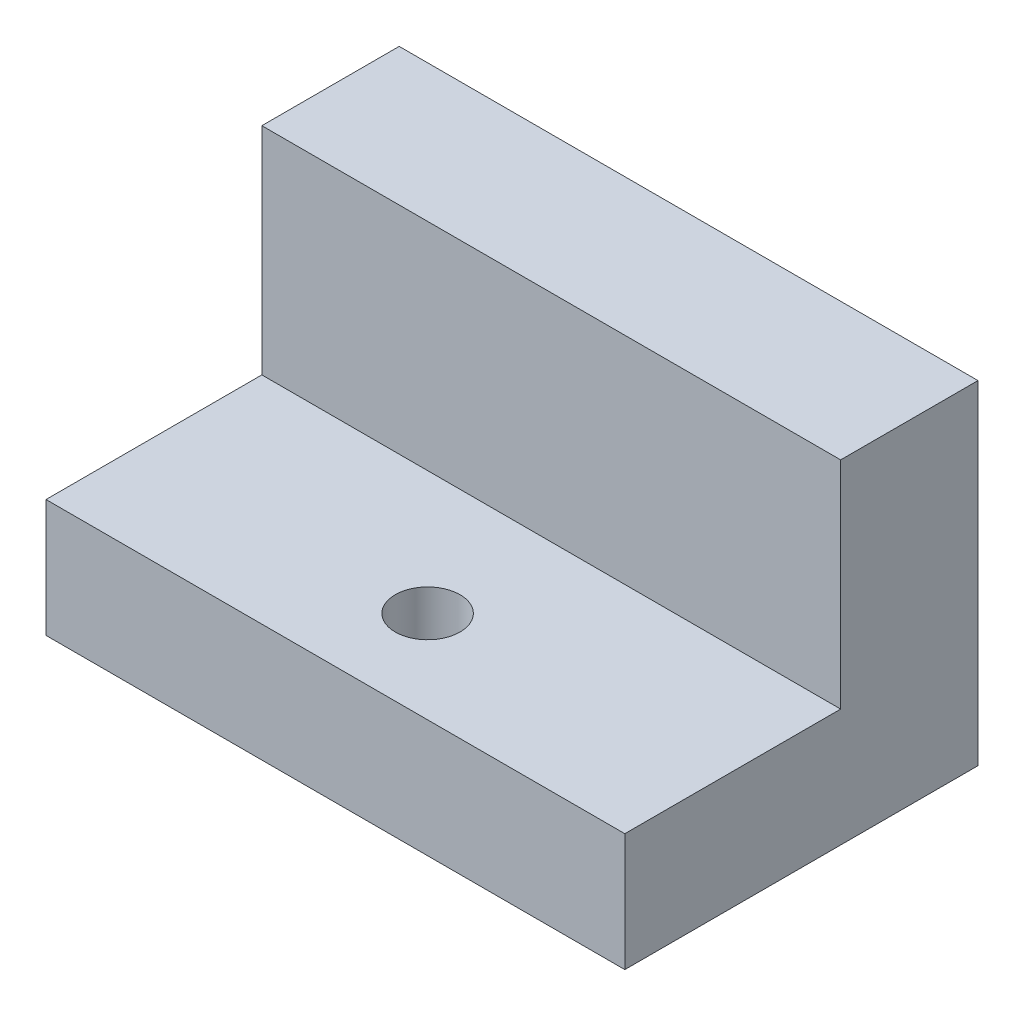
SolidWorks part; units mm, degrees
ref_plane "Front Plane" through (0, 0, 0) normal (0, 0, 1) x (1, 0, 0)
ref_plane "Top Plane" through (0, 0, 0) normal (0, 1, 0) x (1, 0, 0)
ref_plane "Right Plane" through (0, 0, 0) normal (1, 0, 0) x (0, 0, -1)
sketch "Sketch1" plane through (0, 0, 0) normal (0, 1, 0) x (1, 0, 0)
  line L0 (0, 4) -> (0, -4) construction
  line L1 (-14.75, 4) -> (14.75, 4)
  line L2 (-14.75, 4) -> (-14.75, -4)
  line L3 (-14.75, -4) -> (14.75, -4)
  line L4 (14.75, 4) -> (14.75, -4)
  line L5 (-14.75, 4) -> (14.75, -4) construction
  line L6 (-14.75, -4) -> (14.75, 4) construction
  line L7 (14.75, 4) -> (-14.75, 4)
  line L8 (14.75, 4) -> (14.75, 14)
  line L9 (14.75, 14) -> (-14.75, 14)
  line L10 (-14.75, 4) -> (-14.75, 14)
  line L11 (0, 4) -> (0, -2.6) construction
  circle A0 centre (0, 0.7) radius 1.65
  point P0 (0, 0)
  dimension "D5" = 3.3
  dimension "D6" = 3.3
  dimension "D1" = 29.5
  dimension "D2" = 8
  dimension "D3" = 10
  dimension "D4" = 6.6
extrude "Boss-Extrude1" add sketch "Sketch1" along normal blind 6 contours L10 L1 L8 L9 | L4 L1 L2 L3 A0
sketch "Sketch3" plane through (0, 6, 0) normal (0, 1, 0) x (1, 0, 0)
  line L0 (14.75, -4) -> (14.75, 14) construction
  line L1 (-14.75, 14) -> (14.75, 14)
  line L2 (-14.75, 14) -> (-14.75, 7)
  line L3 (-14.75, 7) -> (14.75, 7)
  line L4 (14.75, 14) -> (14.75, 7)
  dimension "D1" = 7
extrude "Boss-Extrude3" add sketch "Sketch3" along normal blind 11
